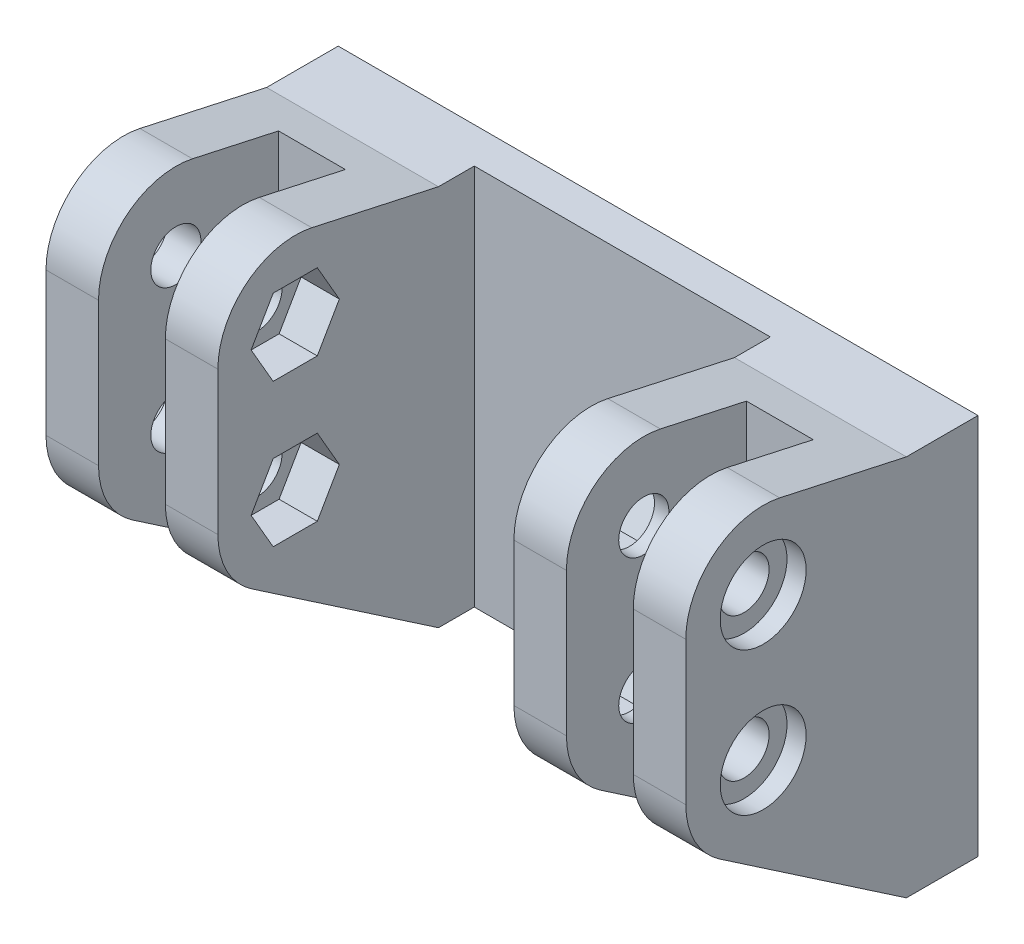
SolidWorks part; units mm, degrees
material "ABS"
ref_plane "Front Plane" through (0, 0, 0) normal (0, 0, 1) x (1, 0, 0)
ref_plane "Top Plane" through (0, 0, 0) normal (0, 1, 0) x (1, 0, 0)
ref_plane "Right Plane" through (0, 0, 0) normal (1, 0, 0) x (0, 0, -1)
sketch "Sketch1" plane through (0, 0, 0) normal (1, 0, 0) x (0, 0, -1)
  line L0 (0, 40) -> (0, 0) construction
  line L1 (0, 0) -> (5, 0)
  line L3 (0, 40) -> (5, 40)
  line L4 (5, 0) -> (5, 40)
  line L5 (0, 40) -> (-2.5, 40)
  line L7 (0, 0) -> (-2.5, 0)
  line L8 (-2.5, 40) -> (-2.5, 0) construction
  line L9 (-25.6, 35) -> (-25.6, 20)
  line L10 (-2.5, 0) -> (-22.0558, 13.3026)
  line L11 (-2.5, 40) -> (-15.7632, 42.9116)
  circle A0 centre (-17.5, 35) radius 2.625
  arc A1 (-15.7632, 42.9116) -> (-25.6, 35) centre (-17.5, 35) ccw
  circle A2 centre (-17.5, 20) radius 2.625
  arc A3 (-25.6, 20) -> (-22.0558, 13.3026) centre (-17.5, 20) ccw
  point P7 (-17.5, 20)
  point P8 (-17.5, 35)
  dimension "D7" = 5.25
  dimension "D8" = 8.1
  dimension "D9" = 5.25
  dimension "D10" = 8.1
  dimension "D1" = 5
  dimension "D2" = 2.5
  dimension "D3" = 40
  dimension "D4" = 15
  dimension "D5" = 20
  dimension "D6" = 15
extrude "Boss-Extrude1" add sketch "Sketch1" along normal blind 18
ref_plane "Plane2" through (0, 0, 0) normal (-1, 0, 0) x (0, 0, 1)
sketch "Sketch2" plane through (0, 0, 0) normal (-1, 0, 0) x (0, 0, 1)
  line L0 (-5, 40) -> (2.5, 40) construction
  line L1 (-5, 0) -> (-1.25, 0)
  line L2 (-5, 0) -> (-5, 40)
  line L3 (-5, 40) -> (-1.25, 40)
  line L4 (-1.25, 0) -> (-1.25, 40)
extrude "Boss-Extrude2" add sketch "Sketch2" along normal blind 15.5
sketch "Sketch3" plane through (0, 0, 0) normal (1, 0, 0) x (0, 0, -1)
  line L1 (-12.8812, 35) -> (-15.1906, 39)
  line L2 (-15.1906, 39) -> (-19.8094, 39)
  line L3 (-19.8094, 39) -> (-22.1188, 35)
  line L4 (-22.1188, 35) -> (-19.8094, 31)
  line L5 (-19.8094, 31) -> (-15.1906, 31)
  line L6 (-15.1906, 31) -> (-12.8812, 35)
  line L7 (-12.8812, 20) -> (-15.1906, 24)
  line L8 (-15.1906, 24) -> (-19.8094, 24)
  line L9 (-19.8094, 24) -> (-22.1188, 20)
  line L10 (-22.1188, 20) -> (-19.8094, 16)
  line L11 (-19.8094, 16) -> (-15.1906, 16)
  line L12 (-15.1906, 16) -> (-12.8812, 20)
  circle A0 centre (-17.5, 35) radius 3.1 construction
  circle A1 centre (-17.5, 35) radius 4 construction
  circle A2 centre (-17.5, 20) radius 4 construction
  dimension "D1" = 8
  dimension "D2" = 8
ref_plane "Plane1" through (9, 0, 0) normal (1, 0, 0) x (0, 0, -1)
sketch "Sketch4" plane through (9, 0, 0) normal (1, 0, 0) x (0, 0, -1)
  line L0 (1.25, 0) -> (1.25, 40) construction
  line L1 (-6.75, 43.493) -> (-32.9351, 43.493)
  line L2 (-6.75, 43.493) -> (-6.75, 0)
  line L3 (-6.75, 0) -> (-32.9351, 0)
  line L4 (-32.9351, 43.493) -> (-32.9351, 0)
  dimension "D1" = 8
extrude "Cut-Extrude2" cut sketch "Sketch4" against normal blind 3.5 and the other way blind 3.5
sketch "Sketch5" plane through (0, 0, -1.25) normal (0, 0, 1) x (1, 0, 0)
  line L0 (-15.5, 40) -> (-15.5, 0) construction
  line L1 (-15.5, 23.302) -> (-15.5, 16.698)
  arc A0 (-15.5, 16.698) -> (-15.5, 23.302) centre (-15.5, 20) ccw
  dimension "D1" = 6.604
extrude "Cut-Extrude3" cut sketch "Sketch5" against normal up to surface (3.75 mm away) up to face at (1.25, 20, -5)
extrude "Cut-Extrude4" cut sketch "Sketch3" along normal blind 4
sketch "Sketch6" plane through (18, 0, 0) normal (1, 0, 0) x (0, 0, -1)
  circle A0 centre (-17.5, 20) radius 4.5
  circle A1 centre (-17.5, 35) radius 4.5
  dimension "D1" = 9
  dimension "D2" = 9
extrude "Cut-Extrude5" cut sketch "Sketch6" against normal blind 2
mirror "Mirror2" about plane through (-15.5, 0, 0) normal (1, 0, 0) of bodies 109 106
